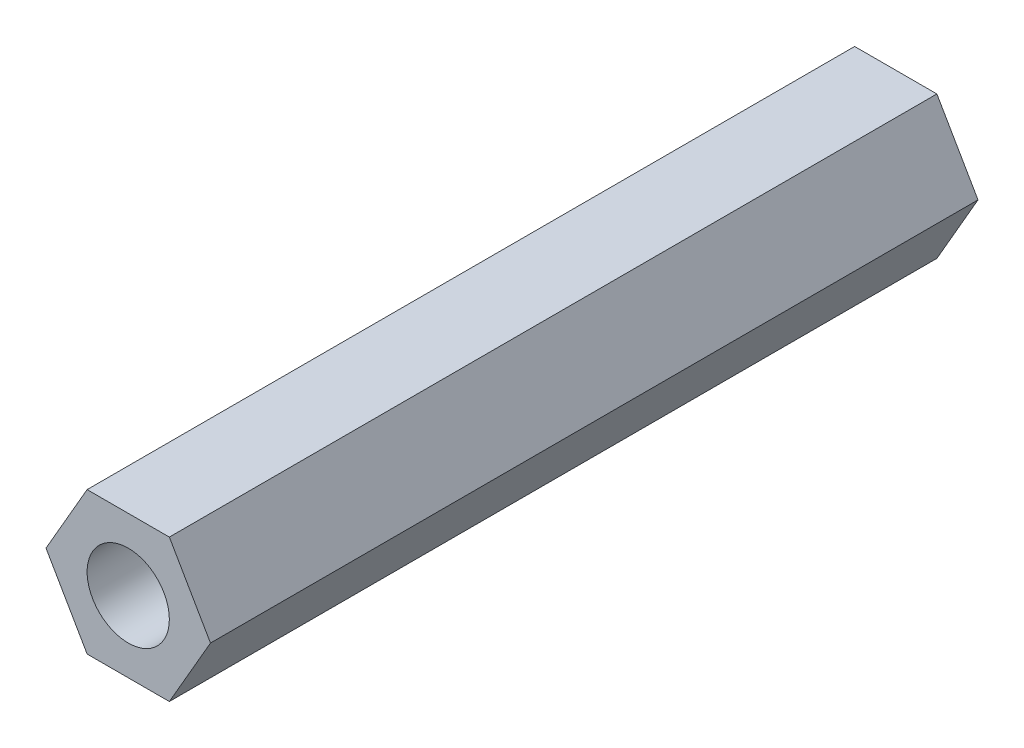
SolidWorks part; units mm, degrees
ref_plane "Спереди" through (0, 0, 0) normal (0, 0, 1) x (1, 0, 0)
ref_plane "Сверху" through (0, 0, 0) normal (0, 1, 0) x (1, 0, 0)
ref_plane "Справа" through (0, 0, 0) normal (1, 0, 0) x (0, 0, -1)
sketch "Эскиз1" plane through (0, 0, 0) normal (0, 0, 1) x (1, 0, 0)
  line L1 (3, 0) -> (1.5, 2.5981)
  line L2 (1.5, 2.5981) -> (-1.5, 2.5981)
  line L3 (-1.5, 2.5981) -> (-3, 0)
  line L4 (-3, 0) -> (-1.5, -2.5981)
  line L5 (-1.5, -2.5981) -> (1.5, -2.5981)
  line L6 (1.5, -2.5981) -> (3, 0)
  circle A0 centre (0, 0) radius 2.5981 construction
  circle A1 centre (0, 0) radius 1.5
extrude "Бобышка-Вытянуть1" add sketch "Эскиз1" along normal blind 28
